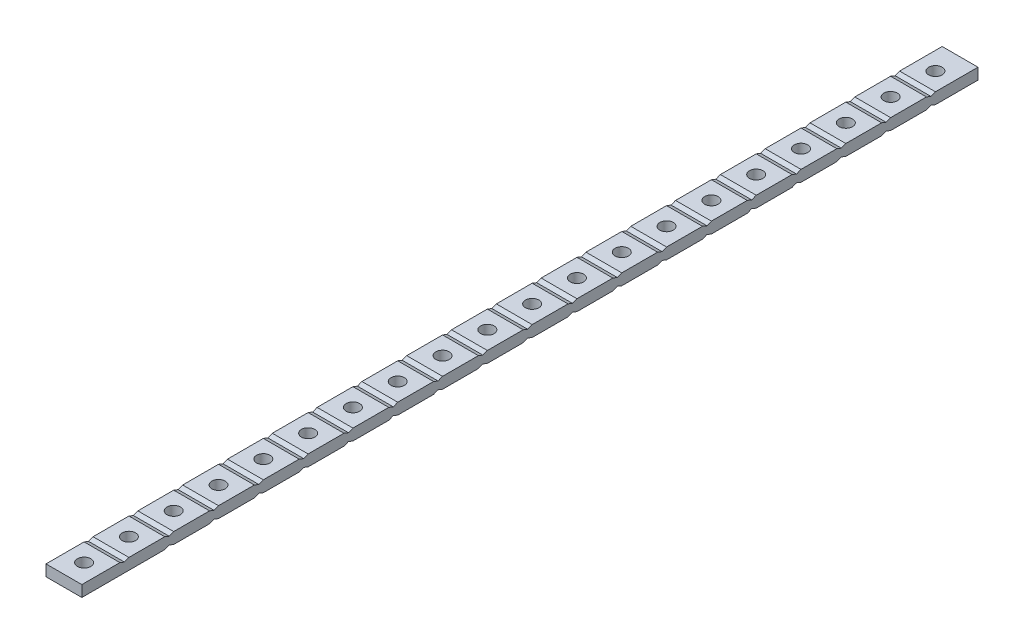
SolidWorks part; units mm, degrees
ref_plane "Front Plane" through (0, 0, 0) normal (0, 0, 1) x (1, 0, 0)
ref_plane "Top Plane" through (0, 0, 0) normal (0, 1, 0) x (1, 0, 0)
ref_plane "Right Plane" through (0, 0, 0) normal (1, 0, 0) x (0, 0, -1)
sketch "Sketch1" plane through (0, 0, 0) normal (0, 1, 0) x (1, 0, 0)
  line L1 (-4, 195.6) -> (4, 195.6)
  line L2 (-4, 195.6) -> (-4, -4.4)
  line L3 (-4, -4.4) -> (4, -4.4)
  line L4 (4, 195.6) -> (4, -4.4)
  point P0 (0, 0)
  dimension "D2" = 200
  dimension "D1" = 8
extrude "Boss-Extrude1" add sketch "Sketch1" along normal blind 2.5
sketch "Sketch2" plane through (0, 2.5, 0) normal (0, 1, 0) x (1, 0, 0)
  line L2 (-4, -4.4) -> (4, -4.4) construction
  line L3 (0, 3.0275) -> (0, -8.059) construction
  circle A1 centre (0, 0.1) radius 1.5
  circle A2 centre (0, 10.1) radius 1.5
  circle A3 centre (0, 20.1) radius 1.5
  circle A4 centre (0, 30.1) radius 1.5
  circle A5 centre (0, 40.1) radius 1.5
  circle A6 centre (0, 50.1) radius 1.5
  circle A7 centre (0, 60.1) radius 1.5
  circle A8 centre (0, 70.1) radius 1.5
  circle A9 centre (0, 80.1) radius 1.5
  circle A10 centre (0, 90.1) radius 1.5
  circle A11 centre (0, 100.1) radius 1.5
  circle A12 centre (0, 110.1) radius 1.5
  circle A13 centre (0, 120.1) radius 1.5
  circle A14 centre (0, 130.1) radius 1.5
  circle A15 centre (0, 140.1) radius 1.5
  circle A16 centre (0, 150.1) radius 1.5
  circle A17 centre (0, 160.1) radius 1.5
  circle A18 centre (0, 170.1) radius 1.5
  circle A19 centre (0, 180.1) radius 1.5
  circle A20 centre (0, 190.1) radius 1.5
  dimension "D1" = 3
  dimension "D2" = 3
extrude "Cut-Extrude1" cut sketch "Sketch2" against normal through all
sketch "Sketch3" plane through (4, 0, 0) normal (1, 0, 0) x (0, 0, -1)
  line L0 (-4.4, 2.5) -> (-4.4, 0) construction
  line L1 (-4.4, 2.5) -> (-4.4, 0)
  line L2 (5.1, -2.5897) -> (5.1, 8.2501) construction
  line L3 (4.1, 2.5) -> (5.1, 2.1)
  line L4 (-4.4, 2.5) -> (195.6, 2.5) construction
  line L5 (5.1, 2.1) -> (6.1, 2.5)
  line L6 (6.1, 2.5) -> (4.1, 2.5)
  line L7 (-4.4, 1.25) -> (-1.5898, 1.25) construction
  line L8 (5.1, 0.4) -> (6.1, 0)
  line L9 (4.1, 0) -> (5.1, 0.4)
  line L10 (6.1, 0) -> (4.1, 0)
  line L11 (16.1, 2.5) -> (14.1, 2.5)
  line L12 (14.1, 2.5) -> (15.1, 2.1)
  line L13 (15.1, 2.1) -> (16.1, 2.5)
  line L14 (15.1, 0.4) -> (16.1, 0)
  line L15 (16.1, 0) -> (14.1, 0)
  line L16 (14.1, 0) -> (15.1, 0.4)
  line L17 (26.1, 2.5) -> (24.1, 2.5)
  line L18 (24.1, 2.5) -> (25.1, 2.1)
  line L19 (25.1, 2.1) -> (26.1, 2.5)
  line L20 (25.1, 0.4) -> (26.1, 0)
  line L21 (26.1, 0) -> (24.1, 0)
  line L22 (24.1, 0) -> (25.1, 0.4)
  line L23 (36.1, 2.5) -> (34.1, 2.5)
  line L24 (34.1, 2.5) -> (35.1, 2.1)
  line L25 (35.1, 2.1) -> (36.1, 2.5)
  line L26 (35.1, 0.4) -> (36.1, 0)
  line L27 (36.1, 0) -> (34.1, 0)
  line L28 (34.1, 0) -> (35.1, 0.4)
  line L29 (46.1, 2.5) -> (44.1, 2.5)
  line L30 (44.1, 2.5) -> (45.1, 2.1)
  line L31 (45.1, 2.1) -> (46.1, 2.5)
  line L32 (45.1, 0.4) -> (46.1, 0)
  line L33 (46.1, 0) -> (44.1, 0)
  line L34 (44.1, 0) -> (45.1, 0.4)
  line L35 (56.1, 2.5) -> (54.1, 2.5)
  line L36 (54.1, 2.5) -> (55.1, 2.1)
  line L37 (55.1, 2.1) -> (56.1, 2.5)
  line L38 (55.1, 0.4) -> (56.1, 0)
  line L39 (56.1, 0) -> (54.1, 0)
  line L40 (54.1, 0) -> (55.1, 0.4)
  line L41 (66.1, 2.5) -> (64.1, 2.5)
  line L42 (64.1, 2.5) -> (65.1, 2.1)
  line L43 (65.1, 2.1) -> (66.1, 2.5)
  line L44 (65.1, 0.4) -> (66.1, 0)
  line L45 (66.1, 0) -> (64.1, 0)
  line L46 (64.1, 0) -> (65.1, 0.4)
  line L47 (76.1, 2.5) -> (74.1, 2.5)
  line L48 (74.1, 2.5) -> (75.1, 2.1)
  line L49 (75.1, 2.1) -> (76.1, 2.5)
  line L50 (75.1, 0.4) -> (76.1, 0)
  line L51 (76.1, 0) -> (74.1, 0)
  line L52 (74.1, 0) -> (75.1, 0.4)
  line L53 (86.1, 2.5) -> (84.1, 2.5)
  line L54 (84.1, 2.5) -> (85.1, 2.1)
  line L55 (85.1, 2.1) -> (86.1, 2.5)
  line L56 (85.1, 0.4) -> (86.1, 0)
  line L57 (86.1, 0) -> (84.1, 0)
  line L58 (84.1, 0) -> (85.1, 0.4)
  line L59 (96.1, 2.5) -> (94.1, 2.5)
  line L60 (94.1, 2.5) -> (95.1, 2.1)
  line L61 (95.1, 2.1) -> (96.1, 2.5)
  line L62 (95.1, 0.4) -> (96.1, 0)
  line L63 (96.1, 0) -> (94.1, 0)
  line L64 (94.1, 0) -> (95.1, 0.4)
  line L65 (106.1, 2.5) -> (104.1, 2.5)
  line L66 (104.1, 2.5) -> (105.1, 2.1)
  line L67 (105.1, 2.1) -> (106.1, 2.5)
  line L68 (105.1, 0.4) -> (106.1, 0)
  line L69 (106.1, 0) -> (104.1, 0)
  line L70 (104.1, 0) -> (105.1, 0.4)
  line L71 (116.1, 2.5) -> (114.1, 2.5)
  line L72 (114.1, 2.5) -> (115.1, 2.1)
  line L73 (115.1, 2.1) -> (116.1, 2.5)
  line L74 (115.1, 0.4) -> (116.1, 0)
  line L75 (116.1, 0) -> (114.1, 0)
  line L76 (114.1, 0) -> (115.1, 0.4)
  line L77 (126.1, 2.5) -> (124.1, 2.5)
  line L78 (124.1, 2.5) -> (125.1, 2.1)
  line L79 (125.1, 2.1) -> (126.1, 2.5)
  line L80 (125.1, 0.4) -> (126.1, 0)
  line L81 (126.1, 0) -> (124.1, 0)
  line L82 (124.1, 0) -> (125.1, 0.4)
  line L83 (136.1, 2.5) -> (134.1, 2.5)
  line L84 (134.1, 2.5) -> (135.1, 2.1)
  line L85 (135.1, 2.1) -> (136.1, 2.5)
  line L86 (135.1, 0.4) -> (136.1, 0)
  line L87 (136.1, 0) -> (134.1, 0)
  line L88 (134.1, 0) -> (135.1, 0.4)
  line L89 (146.1, 2.5) -> (144.1, 2.5)
  line L90 (144.1, 2.5) -> (145.1, 2.1)
  line L91 (145.1, 2.1) -> (146.1, 2.5)
  line L92 (145.1, 0.4) -> (146.1, 0)
  line L93 (146.1, 0) -> (144.1, 0)
  line L94 (144.1, 0) -> (145.1, 0.4)
  line L95 (156.1, 2.5) -> (154.1, 2.5)
  line L96 (154.1, 2.5) -> (155.1, 2.1)
  line L97 (155.1, 2.1) -> (156.1, 2.5)
  line L98 (155.1, 0.4) -> (156.1, 0)
  line L99 (156.1, 0) -> (154.1, 0)
  line L100 (154.1, 0) -> (155.1, 0.4)
  line L101 (166.1, 2.5) -> (164.1, 2.5)
  line L102 (164.1, 2.5) -> (165.1, 2.1)
  line L103 (165.1, 2.1) -> (166.1, 2.5)
  line L104 (165.1, 0.4) -> (166.1, 0)
  line L105 (166.1, 0) -> (164.1, 0)
  line L106 (164.1, 0) -> (165.1, 0.4)
  line L107 (176.1, 2.5) -> (174.1, 2.5)
  line L108 (174.1, 2.5) -> (175.1, 2.1)
  line L109 (175.1, 2.1) -> (176.1, 2.5)
  line L110 (175.1, 0.4) -> (176.1, 0)
  line L111 (176.1, 0) -> (174.1, 0)
  line L112 (174.1, 0) -> (175.1, 0.4)
  line L113 (186.1, 2.5) -> (184.1, 2.5)
  line L114 (184.1, 2.5) -> (185.1, 2.1)
  line L115 (185.1, 2.1) -> (186.1, 2.5)
  line L116 (185.1, 0.4) -> (186.1, 0)
  line L117 (186.1, 0) -> (184.1, 0)
  line L118 (184.1, 0) -> (185.1, 0.4)
  point P14 (0, 0)
  point P15 (0, 0)
  point P124 (0, 0)
  point P125 (0, 0)
  point P126 (0, 0)
  point P127 (0, 0)
  line M3 (-4.4, 0) -> (195.6, 0)
  line M5 (195.6, 2.5) -> (-4.4, 2.5)
  dimension "D1" = 9.5
  dimension "D2" = 0.4
  dimension "D3" = 2
extrude "Cut-Extrude2" cut sketch "Sketch3" against normal through all contours L18 L19 M5 | L28 L26 M3 | L34 L32 M3 | L40 L38 M3 | L6 L3 L5 | L11 L12 L13 | L14 L15 L16 | L20 L21 L22 | L23 L24 L25 | L29 L30 L31 | L35 L36 L37 | L42 L43 L41 | L45 L46 L44 | L47 L48 L49 | L50 L51 L52 | L53 L54 L55 | L56 L57 L58 | L59 L60 L61 | L62 L63 L64 | L65 L66 L67 | L68 L69 L70 | L71 L72 L73 | L74 L75 L76 | L77 L78 L79 | L80 L81 L82 | L83 L84 L85 | L86 L87 L88 | L89 L90 L91 | L92 L93 L94 | L95 L96 L97 | L98 L99 L100 | L101 L102 L103 | L105 L106 L104 | L107 L108 L109 | L110 L111 L112 | L113 L114 L115 | L116 L117 L118
